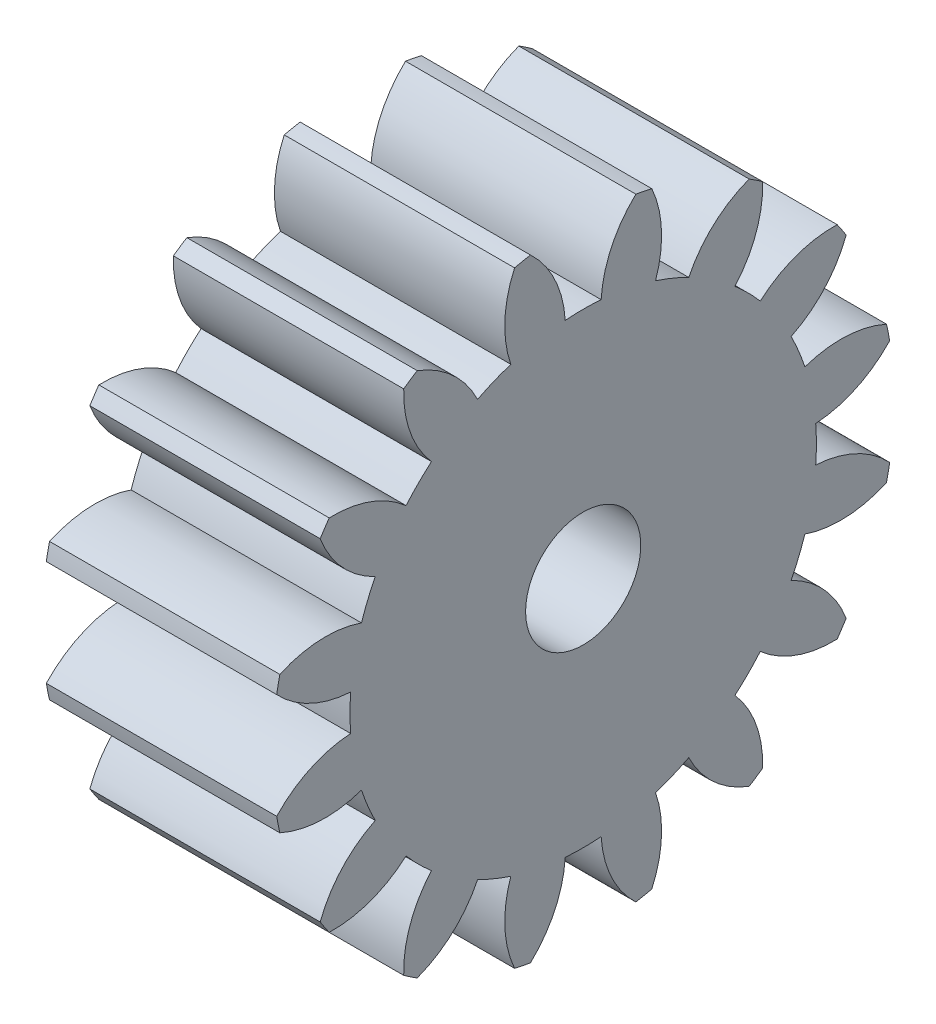
SolidWorks part; units mm, degrees
ref_plane "Plane1" through (0, 0, 0) normal (0, 0, 1) x (1, 0, 0)
ref_plane "Plane2" through (0, 0, 0) normal (0, 1, 0) x (1, 0, 0)
ref_plane "Plane3" through (0, 0, 0) normal (1, 0, 0) x (0, 0, -1)
sketch "HoldingSke" plane through (0, 0, 0) normal (0, 1, 0) x (1, 0, 0)
  line L0 (0, 0) -> (0.6408, -0.1838)
  line L1 (-15, 0) -> (100, 0) construction
  line L2 (0, 0) -> (-2.1039, 2.3779)
  line L3 (0, 0) -> (-11.863, 4.5341)
  line L4 (0, 0) -> (8.3015, 2.3804)
  line L5 (0, 0) -> (-46.8476, -17.4728)
  line L6 (0, 0) -> (-8.2896, -5.593)
  line L7 (-2.1039, 2.3779) -> (8.6586, 51.2059)
  line L8 (-76.2, 54.61) -> (-75.3, 54.61)
  line L9 (-71.009, 38.7566) -> (-53.1078, 45.2721)
  line L10 (-76.2, 71.12) -> (104.1128, 71.12)
  line L11 (0, 0) -> (-10, 0)
  line L12 (-76.2, 101.6) -> (-76.147, 101.6)
  line L13 (24.9733, 27.94) -> (52.9518, 28.4284)
  line L14 (24.9733, 27.94) -> (24.9743, 27.94)
  line L15 (24.9733, 27.94) -> (100.4006, 29.5858)
  line L16 (-63.627, -1.5) -> (-12.827, -1.5)
  circle A0 centre (0, 0) radius 2.5
  circle A1 centre (0, 0) radius 10.124
  circle A2 centre (0, 0) radius 37.5
  circle A3 centre (0, 0) radius 2.5
  dimension "MHD" = 20.248
  dimension "Hub_dia" = 75
  dimension "Bore" = 5
  dimension "MBD" = 5
  dimension "Num_teeth" = 16
  dimension "Pitch" = 0.6667
  dimension "Overall_len" = 50
  dimension "Show_teeth" = 16
  dimension "Thickness" = 10
  dimension "OAL" = 50.0001
  dimension "T_dim" = 0.9
  dimension "Ap" = 20
  dimension "H" = 19.05
  dimension "Pitch_radius" = 180.3128
  dimension "Width" = 10
  dimension "Backlash" = 0.053
  dimension "Addendum_fac" = 1
  dimension "Dedendum_fac" = 1.25
  dimension "Clearance_fac" = 0.25
  dimension "Dedendum_add" = 0.001
  dimension "Module" = 1.5
sketch "BasProSke" plane through (0, 0, 0) normal (0, 1, 0) x (1, 0, 0)
  line L0 (-10, 0) -> (60, 0) construction
  line L1 (0, 0) -> (0, 13.5)
  line L2 (0, 0) -> (10, 0)
  line L3 (10, 0) -> (10, 13.5)
  line L4 (10, 13.5) -> (0, 13.5)
  dimension "Thickness" = 10
  dimension "Diameter" = 27
revolve "Base-Revolve" add sketch "BasProSke" angle 360 about L0
sketch "TooCutSke" plane through (0, 0, 0) normal (1, 0, 0) x (0, 0, -1)
  line L1 (0, 0) -> (0, 107) construction
  line L2 (0, 0) -> (-1.2689, 11.9327) construction
  line L3 (0, 0) -> (-4.663, 23.4427) construction
  line L4 (-1.2689, 11.9327) -> (-2.3315, 11.7214) construction
  arc A0 (0.7798, 10.0939) -> (-0.7798, 10.0939) centre (0, 0) ccw
  arc A1 (2.3105, 13.3266) -> (-2.3105, 13.3266) centre (0, 0) ccw
  circle A2 centre (0, 0) radius 12 construction
  circle A3 centre (0, 0) radius 11.2763 construction
  arc A4 (-0.7798, 10.0939) -> (-2.3105, 13.3266) centre (-5.571, 9.804) ccw
  arc A5 (2.3105, 13.3266) -> (0.7798, 10.0939) centre (5.571, 9.804) ccw
  dimension "Root_dia" = 20.248
  dimension "Overcut_dia" = 27.0508
  dimension "Pitch_dia" = 24
  dimension "Base_dia" = 22.5526
  dimension "Flank_rad" = 4.8
  dimension "Half_ang" = 11.25
  dimension "Half_CT" = 1.0835
extrude "ToothCut" cut sketch "TooCutSke" along normal through all
fillet "Breaks" [suppressed] radius 0.03
fillet "RootFillets" [suppressed] radius 0.376
pattern_circular "TeethCuts" count 16 every 22.5 about axis through (-10, 0, 0) along (1, 0, 0) of "ToothCut", "RootFillets", "Breaks"
sketch "HubNeaOneSke" plane through (0, 0, 0) normal (-1, 0, 0) x (0, 0, 1)
  circle A0 centre (0, 0) radius 10.124
  dimension "Diameter" = 20.248
extrude "HubNearOne" [suppressed] add sketch "HubNeaOneSke" along normal blind 40.0001
sketch "HubNeaBotSke" plane through (0, 0, 0) normal (-1, 0, 0) x (0, 0, 1)
  circle A0 centre (0, 0) radius 10.124
  dimension "Diameter" = 20.248
extrude "HubNearBoth" [suppressed] add sketch "HubNeaBotSke" along normal blind 20
ref_plane "FarPln" through (10, 0, 0) normal (1, 0, 0) x (0, 0, -1)
sketch "HubFarSke" plane through (10, 0, 0) normal (1, 0, 0) x (0, 0, -1)
  circle A0 centre (0, 0) radius 10.124
  dimension "Diameter" = 20.248
extrude "HubFar" [suppressed] add sketch "HubFarSke" along normal blind 20
sketch "BorSke" plane through (0, 0, 0) normal (1, 0, 0) x (0, 0, -1)
  circle A0 centre (0, 0) radius 2.5
  dimension "Diameter" = 5
extrude "Bore" cut sketch "BorSke" along normal mid plane 100.0001
sketch "KeySke" plane through (0, 0, 0) normal (1, 0, 0) x (0, 0, -1)
  line L0 (-1, 0) -> (-1, 3.4)
  line L1 (-1, 3.4) -> (1, 3.4)
  line L2 (1, 3.4) -> (1, 0)
  line L3 (0, 0) -> (0, 34) construction
  line L4 (-1, 0) -> (1, 0)
  dimension "Offset" = 3.4
  dimension "Width" = 2
extrude "Keyway" [suppressed] cut sketch "KeySke" along normal mid plane 100.0001
pattern_circular "Keyway2" [suppressed] count 2 every 90 about axis through (-10, 0, 0) along (1, 0, 0)
equation "' \"Module@HoldingSke\" = 6.35"
equation "' \"Num_teeth@HoldingSke\" = 12"
equation "' \"Ap@HoldingSke\" =  20"
equation "' \"Ap@HoldingSke\" = 20"
equation "' \"Width@HoldingSke\" = 0.5 * 25.4"
equation "' \"Hub_dia@HoldingSke\"= 1 * 25.4"
equation "' \"Hub_dia@HoldingSke\" = 1 * 25.4"
equation "' \"Overall_len@HoldingSke\" = 1.0 * 25.4"
equation "' \"Bore@HoldingSke\" = 0.75 * 25.4"
equation "' \"T_dim@HoldingSke\" = 0.1 * 25.4"
equation "' \"Width@KeySke\" = 0.25 * 25.4"
equation "' \"Show_teeth@HoldingSke\" = 13"
equation "' \"Backlash@HoldingSke\" = 0.009 * 25.4"
equation "' \"Addendum_fac@HoldingSke\" = 1.0"
equation "' \"Dedendum_fac@HoldingSke\" = 1.25"
equation "' \"Dedendum_add@HoldingSke\" = 0.00005 * 25.4"
equation "' \"Clearance_fac@HoldingSke\" = 0.25"
equation "\"Pitch@HoldingSke\" = 1 / \"Module@HoldingSke\""
equation "\"Overcut_dia@TooCutSke\" = (\"Num_teeth@HoldingSke\" + 2 * \"Addendum_fac@HoldingSke\") / \"Pitch@HoldingSke\" + 0.002 * 25.4"
equation "\"Pitch_dia@TooCutSke\" = \"Num_teeth@HoldingSke\" / \"Pitch@HoldingSke\""
equation "\"Base_dia@TooCutSke\" = \"Num_teeth@HoldingSke\" / \"Pitch@HoldingSke\" * cos((\"Ap@HoldingSke\"  * 3.14159265 / 180))"
equation "\"Root_dia@TooCutSke\" = (\"Num_teeth@HoldingSke\" + 2) / \"Pitch@HoldingSke\" - 2 * (\"Addendum_fac@HoldingSke\" + \"Dedendum_fac@HoldingSke\") / \"Pitch@HoldingSke\" - \"Dedendum_add@HoldingSke\" * 2"
equation "\"Half_ang@TooCutSke\" = 180 / \"Num_teeth@HoldingSke\""
equation "\"Half_CT@TooCutSke\" = \"Num_teeth@HoldingSke\" / \"Pitch@HoldingSke\" * sin((3.14159265 / 2 / \"Num_teeth@HoldingSke\")) / 2 - 7 * \"Backlash@HoldingSke\" / 4"
equation "\"Flank_rad@TooCutSke\" = \"Num_teeth@HoldingSke\" / \"Pitch@HoldingSke\" / 5"
equation "\"Radius@RootFillets\" = \"Clearance_fac@HoldingSke\" / \"Pitch@HoldingSke\" + \"Dedendum_add@HoldingSke\""
equation "\"Break_rad@Breaks\" = 0.02 / \"Pitch@HoldingSke\""
equation "\"Thickness@HoldingSke\" = \"Width@HoldingSke\""
equation "\"OAL@HoldingSke\" = \"Thickness@HoldingSke\""
equation "\"MHD@HoldingSke\" = (\"Num_teeth@HoldingSke\" + 2) / \"Pitch@HoldingSke\" - 2 * (\"Addendum_fac@HoldingSke\" + \"Dedendum_fac@HoldingSke\")  / \"Pitch@HoldingSke\" - \"Dedendum_add@HoldingSke\" * 2"
equation "\"MBD@HoldingSke\" = (\"Num_teeth@HoldingSke\" + 2) / \"Pitch@HoldingSke\" - 2 * (\"Addendum_fac@HoldingSke\" + \"Dedendum_fac@HoldingSke\")  / \"Pitch@HoldingSke\" - \"Dedendum_add@HoldingSke\" * 2 - 0.002 * 25.4"
equation "\"MHD@HoldingSke\" = ((sgn( \"MHD@HoldingSke\" - \"Hub_dia@HoldingSke\" )-1)*( \"MHD@HoldingSke\" - \"Hub_dia@HoldingSke\" ))/-2+ \"Hub_dia@HoldingSke\""
equation "\"MBD@HoldingSke\" = ((sgn( \"MBD@HoldingSke\" - \"Bore@HoldingSke\" )-1)*( \"MBD@HoldingSke\" - \"Bore@HoldingSke\" ))/-2+ \"Bore@HoldingSke\""
equation "\"OAL@HoldingSke\" = ((sgn( \"OAL@HoldingSke\" - \"Overall_len@HoldingSke\" )+1)*( \"OAL@HoldingSke\" - \"Overall_len@HoldingSke\" ))/2 + \"Overall_len@HoldingSke\" + 0.000002 * 25.4"
equation "\"Num_teeth@TeethCuts\" = int( \"Show_teeth@HoldingSke\" ) + 1"
equation "\"Num_teeth@TeethCuts\" = ((sgn( \"Num_teeth@TeethCuts\" - \"Num_teeth@HoldingSke\" )-1)*( \"Num_teeth@TeethCuts\" - \"Num_teeth@HoldingSke\" ))/-2+ \"Num_teeth@HoldingSke\""
equation "\"Num_teeth@TeethCuts\" = ((sgn( \"Num_teeth@TeethCuts\" - 2.0)+1)*( \"Num_teeth@TeethCuts\" - 2.0))/2 +2.0"
equation "\"Angle@TeethCuts\" = 360.0 / \"Num_teeth@HoldingSke\""
equation "\"Diameter@BasProSke\" = (\"Num_teeth@HoldingSke\" + 2 * \"Addendum_fac@HoldingSke\") / \"Pitch@HoldingSke\""
equation "\"Thickness@BasProSke\"  = \"Thickness@HoldingSke\""
equation "' \"Fillet_rad@BasProSke\" =  \"Thickness@HoldingSke\" * 0.05"
equation "' \"Fillet_rad@BasProSke\" = \"Thickness@HoldingSke\" * 0.05"
equation "\"MHD@HoldingSke\" = ((sgn( \"MHD@HoldingSke\" - \"Root_dia@TooCutSke\" )-1)*( \"MHD@HoldingSke\" - \"Root_dia@TooCutSke\" ))/-2+ \"Root_dia@TooCutSke\""
equation "\"Diameter@HubNeaOneSke\" = \"MHD@HoldingSke\""
equation "\"Length@HubNearOne\" = \"OAL@HoldingSke\" - \"Thickness@BasProSke\""
equation "\"Diameter@HubNeaBotSke\" = \"MHD@HoldingSke\""
equation "\"Length@HubNearBoth\" = ( \"OAL@HoldingSke\" - \"Thickness@BasProSke\" ) / 2.0"
equation "\"Thickness@FarPln\" = \"Thickness@BasProSke\""
equation "\"Diameter@HubFarSke\" = \"MHD@HoldingSke\""
equation "\"Length@HubFar\" = ( \"OAL@HoldingSke\" - \"Thickness@BasProSke\" ) / 2.0"
equation "\"Diameter@BorSke\" = \"MBD@HoldingSke\""
equation "\"D1@Bore\" = \"OAL@HoldingSke\" * 2.0"
equation "\"D1@Keyway\" = \"OAL@HoldingSke\" * 2.0"
equation "\"Offset@KeySke\" = \"T_dim@HoldingSke\" + \"MBD@HoldingSke\" / 2.0"
